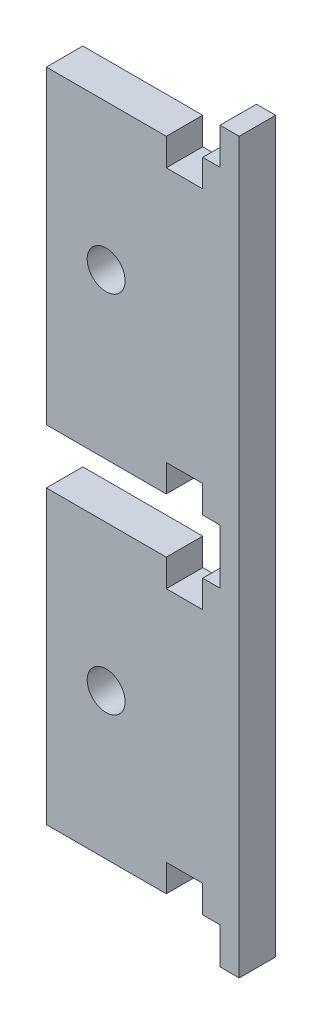
SolidWorks part; units mm, degrees
material "AISI 4130 Steel, annealed at 865C"
ref_plane "X-Y Datum" through (0, 0, 0) normal (0, 0, 1) x (1, 0, 0)
ref_plane "X-Z Datum" through (0, 0, 0) normal (0, 1, 0) x (1, 0, 0)
ref_plane "Y-Z Datum" through (0, 0, 0) normal (1, 0, 0) x (0, 0, -1)
sketch "Sketch2" plane through (0, 0, 0) normal (0, 0, 1) x (1, 0, 0)
  line L0 (34.925, 127) -> (0, 127) construction
  line L1 (0, 0) -> (40.64, 0)
  line L2 (0, 0) -> (0, 127)
  line L3 (0, 127) -> (40.64, 127)
  line L4 (40.64, 0) -> (40.64, 127)
  point P7 (17.4625, 31.75)
  point P8 (17.4625, 95.25)
  dimension "D1" = 40.64
extrude "Boss-Extrude1" add sketch "Sketch2" along normal blind 6.35
hole_wizard "M6 Clearance Hole1" positions "Sketch3" profile "Sketch4" hole size "M6" standard "ANSI Metric" end condition through all
sketch "Sketch3" plane through (0, 0, 6.35) normal (0, 0, 1) x (1, 0, 0)
  point P0 (17.4625, 31.75)
  point P3 (17.4625, 95.25)
sketch "Sketch4" plane through (17.4625, 31.75, 6.35) normal (1, 0, 0) x (0, -1, 0)
  line L0 (0, 0) -> (0, 6.35)
  line L1 (0, 6.35) -> (3.3, 6.35)
  line L2 (3.3, 6.35) -> (3.3, 0)
  line L5 (3.3, 0) -> (0, 0)
  line L11 (0, -6.35) -> (0, 107.95) construction
  dimension "Thru Hole Dia." = 6.6
  dimension "Thru Hole Depth" = 6.35
sketch "Sketch5" plane through (0, 0, 6.35) normal (0, 0, 1) x (1, 0, 0)
  line L0 (7.0505, 127) -> (7.0505, 0)
  line L1 (40.64, 127) -> (0, 127) construction
  line L2 (0, 0) -> (40.64, 0) construction
  circle A0 centre (17.4625, 95.25) radius 3.3 construction
  point P6 (14.1625, 95.25)
  line M4 (0, 127) -> (0, 0)
  line M5 (0, 0) -> (40.64, 0)
  line M7 (40.64, 127) -> (0, 127)
  dimension "D1" = 7.112
extrude "Cut-Extrude1" cut sketch "Sketch5" against normal through all and the other way through all contours L0 M7 M4 M5
sketch "Sketch6" plane through (0, 0, 6.35) normal (0, 0, 1) x (1, 0, 0)
  line L0 (-3.175, 120.65) -> (38.1, 120.65)
  line L1 (38.1, 120.65) -> (38.1, 130.175)
  line L2 (38.1, 130.175) -> (-3.175, 130.175)
  line L3 (-3.175, 130.175) -> (-3.175, 120.65)
  line L4 (0, 123.825) -> (34.925, 123.825)
  line L5 (34.925, 123.825) -> (34.925, 127)
  line L6 (34.925, 127) -> (0, 127)
  line L7 (0, 127) -> (0, 123.825)
  line L8 (0, 123.825) -> (34.925, 123.825)
  line L9 (34.925, 123.825) -> (34.925, 127)
  line L10 (34.925, 127) -> (0, 127)
  line L11 (0, 127) -> (0, 123.825)
  line L12 (0, 60.325) -> (34.925, 60.325)
  line L13 (34.925, 60.325) -> (34.925, 63.5)
  line L14 (34.925, 63.5) -> (0, 63.5)
  line L15 (0, 63.5) -> (0, 60.325)
  line L16 (0, 60.325) -> (34.925, 60.325)
  line L17 (34.925, 60.325) -> (34.925, 63.5)
  line L18 (34.925, 63.5) -> (0, 63.5)
  line L19 (0, 63.5) -> (0, 60.325)
  line L24 (0, 0) -> (34.925, 0)
  line L25 (34.925, 0) -> (34.925, 3.175)
  line L26 (34.925, 3.175) -> (0, 3.175)
  line L27 (0, 3.175) -> (0, 0)
  line L28 (38.1, 66.675) -> (-3.175, 66.675)
  line L29 (-3.175, 66.675) -> (-3.175, 57.15)
  line L30 (-3.175, 57.15) -> (38.1, 57.15)
  line L31 (38.1, 57.15) -> (38.1, 66.675)
  line L32 (38.1, 6.35) -> (-3.175, 6.35)
  line L33 (-3.175, 6.35) -> (-3.175, -3.175)
  line L34 (-3.175, -3.175) -> (38.1, -3.175)
  line L35 (38.1, -3.175) -> (38.1, 6.35)
  line L36 (37.3063, 127) -> (37.3063, 0)
  line L37 (40.64, 127) -> (7.0505, 127) construction
  line L38 (7.0505, 0) -> (40.64, 0) construction
  line M19 (7.0505, 127) -> (7.0505, 0)
  line M20 (7.0505, 0) -> (40.64, 0)
  line M22 (40.64, 127) -> (7.0505, 127)
  dimension "D5" = 2.3813
  dimension "D1" = 0
  dimension "D2" = 0
  dimension "D4" = 3.175
extrude "Cut-Extrude2" cut sketch "Sketch6" against normal through all contours L36 L9 L8 L0 M22 M19 | L8 L9 M22 M19 | L36 L28 L18 L17 L16 L30 M19 | L17 L18 L16 M19 | L36 L32 L26 L25 M19 M20 | L25 L26 M19 M20
sketch "Sketch7" plane through (0, 0, 6.35) normal (0, 0, 1) x (1, 0, 0)
  line L18 (34.29, 120.65) -> (27.94, 120.65)
  line L19 (34.29, 120.65) -> (34.29, 115.8875)
  line L20 (34.29, 115.8875) -> (27.94, 115.8875)
  line L21 (27.94, 120.65) -> (27.94, 115.8875)
  line L22 (34.29, 71.4375) -> (27.94, 71.4375)
  line L23 (34.29, 71.4375) -> (34.29, 66.675)
  line L24 (34.29, 66.675) -> (27.94, 66.675)
  line L25 (27.94, 71.4375) -> (27.94, 66.675)
  line L26 (34.29, 57.15) -> (27.94, 57.15)
  line L27 (34.29, 57.15) -> (34.29, 52.3875)
  line L28 (34.29, 52.3875) -> (27.94, 52.3875)
  line L29 (27.94, 57.15) -> (27.94, 52.3875)
  line L30 (34.29, 11.1125) -> (27.94, 11.1125)
  line L31 (34.29, 11.1125) -> (34.29, 6.35)
  line L32 (34.29, 6.35) -> (27.94, 6.35)
  line L33 (27.94, 11.1125) -> (27.94, 6.35)
extrude "Cut-Extrude3" cut sketch "Sketch7" against normal through all
